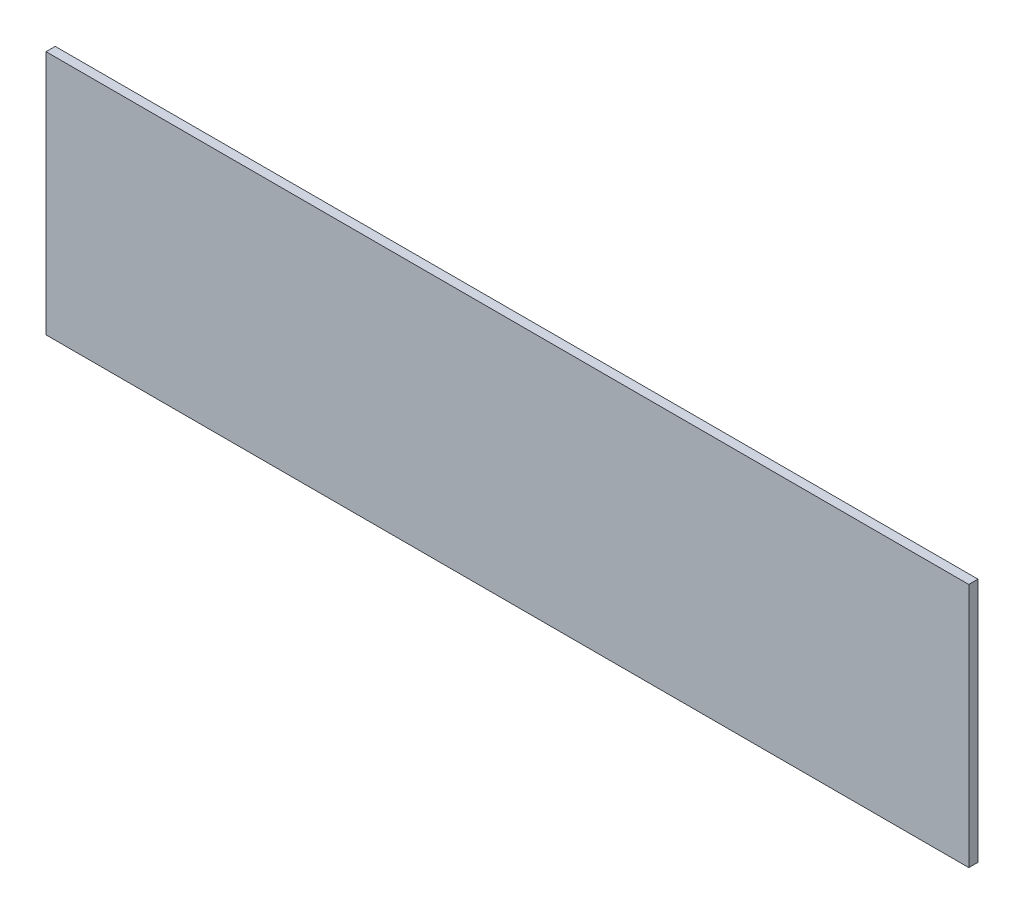
SolidWorks part; units mm, degrees
ref_plane "Plan de face" through (0, 0, 0) normal (0, 0, 1) x (1, 0, 0)
ref_plane "Plan de dessus" through (0, 0, 0) normal (0, 1, 0) x (1, 0, 0)
ref_plane "Plan de droite" through (0, 0, 0) normal (1, 0, 0) x (0, 0, -1)
sketch "Esquisse1" plane through (0, 0, 0) normal (0, 0, 1) x (1, 0, 0)
  line L1 (0, 0) -> (-301, 0)
  line L2 (0, 0) -> (0, 80)
  line L3 (0, 80) -> (-301, 80)
  line L4 (-301, 0) -> (-301, 80)
  dimension "D1" = 80
  dimension "D2" = 301
extrude "Boss.-Extru.1" add sketch "Esquisse1" along normal blind 3
